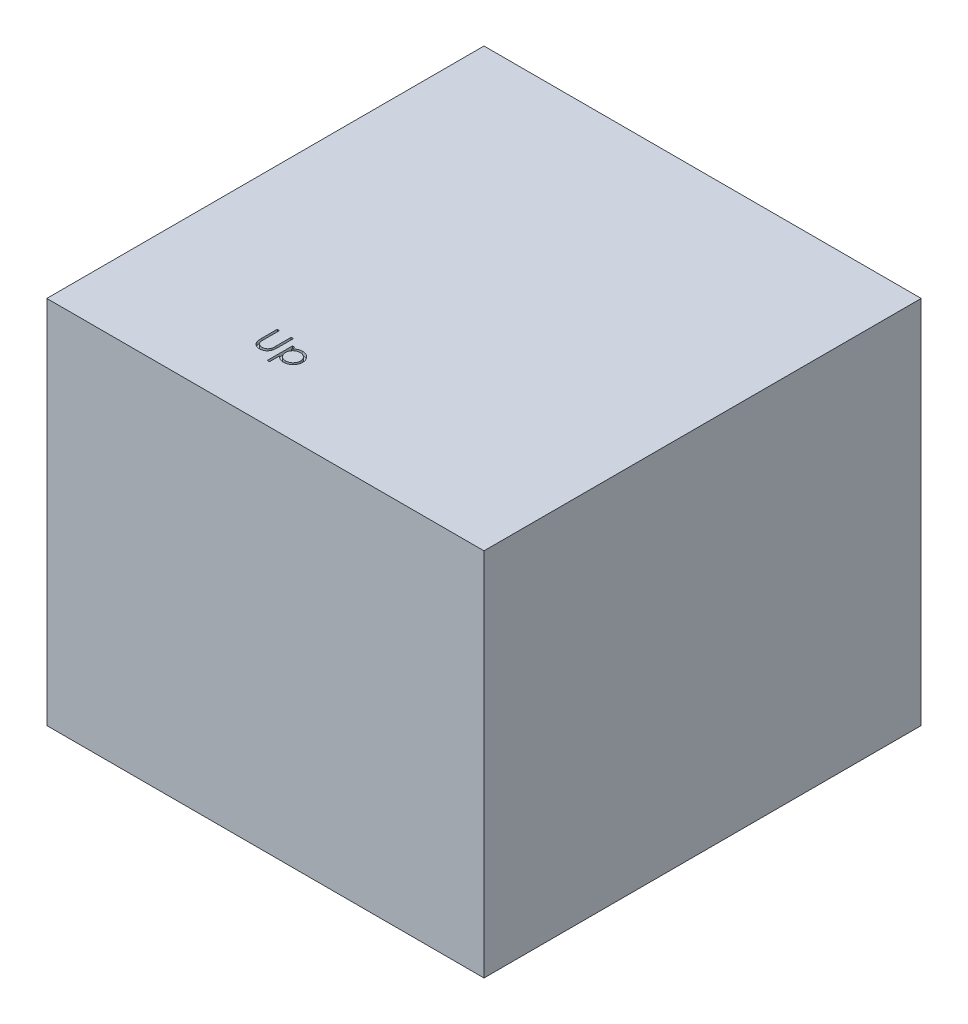
SolidWorks part; units mm, degrees
material "Custom Plastic"
ref_plane "Front Plane" through (0, 0, 0) normal (0, 0, 1) x (1, 0, 0)
ref_plane "Top Plane" through (0, 0, 0) normal (0, 1, 0) x (1, 0, 0)
ref_plane "Right Plane" through (0, 0, 0) normal (1, 0, 0) x (0, 0, -1)
sketch "Sketch1" plane through (0, 0, 0) normal (0, 1, 0) x (1, 0, 0)
  line L1 (165.1, -165.1) -> (-165.1, -165.1)
  line L2 (165.1, -165.1) -> (165.1, 165.1)
  line L3 (165.1, 165.1) -> (-165.1, 165.1)
  line L4 (-165.1, -165.1) -> (-165.1, 165.1)
  line L5 (165.1, -165.1) -> (-165.1, 165.1) construction
  line L6 (165.1, 165.1) -> (-165.1, -165.1) construction
  point P0 (0, 0)
  dimension "D1" = 330.2
  dimension "D2" = 330.2
extrude "Boss-Extrude1" add sketch "Sketch1" along normal blind 279.4
sketch "Sketch2" plane through (0, 279.4, 0) normal (0, 1, 0) x (1, 0, 0)
  text T0 "Up" font "Century Gothic" height in points 72
extrude "Cut-Extrude1" cut sketch "Sketch2" against normal blind 2.54
